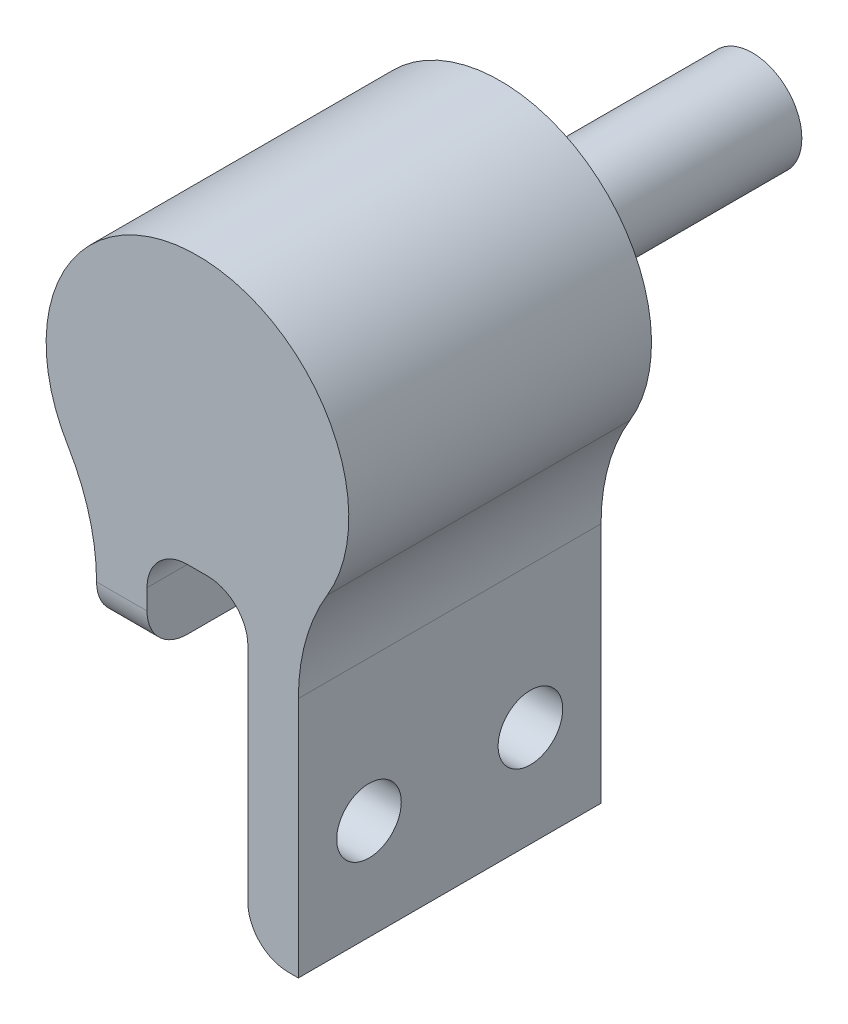
SolidWorks part; units mm, degrees
material "PUR"
ref_plane "Front Plane" through (0, 0, 0) normal (0, 0, 1) x (1, 0, 0)
ref_plane "Top Plane" through (0, 0, 0) normal (0, 1, 0) x (1, 0, 0)
ref_plane "Right Plane" through (0, 0, 0) normal (1, 0, 0) x (0, 0, -1)
sketch "Sketch2" plane through (0, 0, 0) normal (0, 0, 1) x (1, 0, 0)
  line L8 (0, 0) -> (0, -6.0083) construction
  line L9 (0, -6.0083) -> (0, -21.0083) construction
  line L10 (-2.5, -6.0083) -> (-2.5, -21.0083)
  line L11 (2.5, -6.0083) -> (2.5, -21.0083)
  line L12 (-5, -6.0083) -> (-5, -21.0083)
  line L13 (5, -6.0083) -> (5, -21.0083)
  line L14 (-5, -6.0083) -> (-5, -5.5902)
  line L15 (5, -6.0083) -> (5, -5.5902)
  line L16 (-5, -21.0083) -> (-2.5, -21.0083)
  line L17 (2.5, -21.0083) -> (5, -21.0083)
  line L18 (-2.5, -6.0083) -> (2.5, -6.0083)
  arc A0 (5, -5.5902) -> (-5, -5.5902) centre (0, 0) ccw
  dimension "D1" = 2.5
  dimension "D3" = 15
  dimension "D2" = 2.5
  dimension "D4" = 5
  dimension "D5" = 5
  dimension "D6" = 15
extrude "Boss-Extrude1" add sketch "Sketch2" along normal blind 15
sketch "Sketch3" plane through (0, 0, 0) normal (0, 0, -1) x (-1, 0, 0)
  circle A0 centre (0, 0) radius 2.45
  dimension "D1" = 4.9
extrude "Boss-Extrude2" add sketch "Sketch3" along normal blind 12.5
fillet "Fillet2" radius 10 2 edges at (-5, -5.5902, 7.5) (5, -5.5902, 7.5)
sketch "Sketch8" plane through (5, 0, 0) normal (1, 0, 0) x (0, 0, -1)
  line L0 (-15, -21.0083) -> (0, -21.0083) construction
  line L1 (0, -21.0083) -> (0, -9.0139) construction
  circle A0 centre (-3.5, -16.0083) radius 1.6
  dimension "D1" = 3.2
  dimension "D2" = 5
  dimension "D3" = 3.5
extrude "Cut-Extrude6" cut sketch "Sketch8" against normal through all
sketch "Sketch9" plane through (-5, 0, 0) normal (-1, 0, 0) x (0, 0, 1)
  line L1 (15, -21.0083) -> (7.5, -21.0083)
  line L2 (15, -21.0083) -> (15, -11.0083)
  line L3 (15, -11.0083) -> (7.5, -11.0083)
  line L4 (7.5, -21.0083) -> (7.5, -11.0083)
  dimension "D1" = 10
  dimension "D2" = 7.5
extrude "Cut-Extrude7" cut sketch "Sketch9" against normal up to next
sketch "Sketch10" plane through (5, 0, 0) normal (1, 0, 0) x (0, 0, -1)
  line L0 (-15, -21.0083) -> (-15, -9.0139) construction
  line L1 (-15, -21.0083) -> (0, -21.0083) construction
  circle A0 centre (-11.5, -16.0083) radius 1.6
  dimension "D1" = 3.2
  dimension "D2" = 3.5
  dimension "D3" = 5
extrude "Cut-Extrude8" cut sketch "Sketch10" against normal up to next
fillet "Fillet3" radius 1 1 edges at (-2.45, 0, 0)
fillet "Fillet4" radius 2 6 edges at (2.5, -6.0083, 7.5) (-2.5, -6.0083, 7.5) (-3.75, -11.0083, 7.5) (-3.75, -11.0083, 15) (-2.5, -21.0083, 3.75) (2.5, -21.0083, 7.5)
